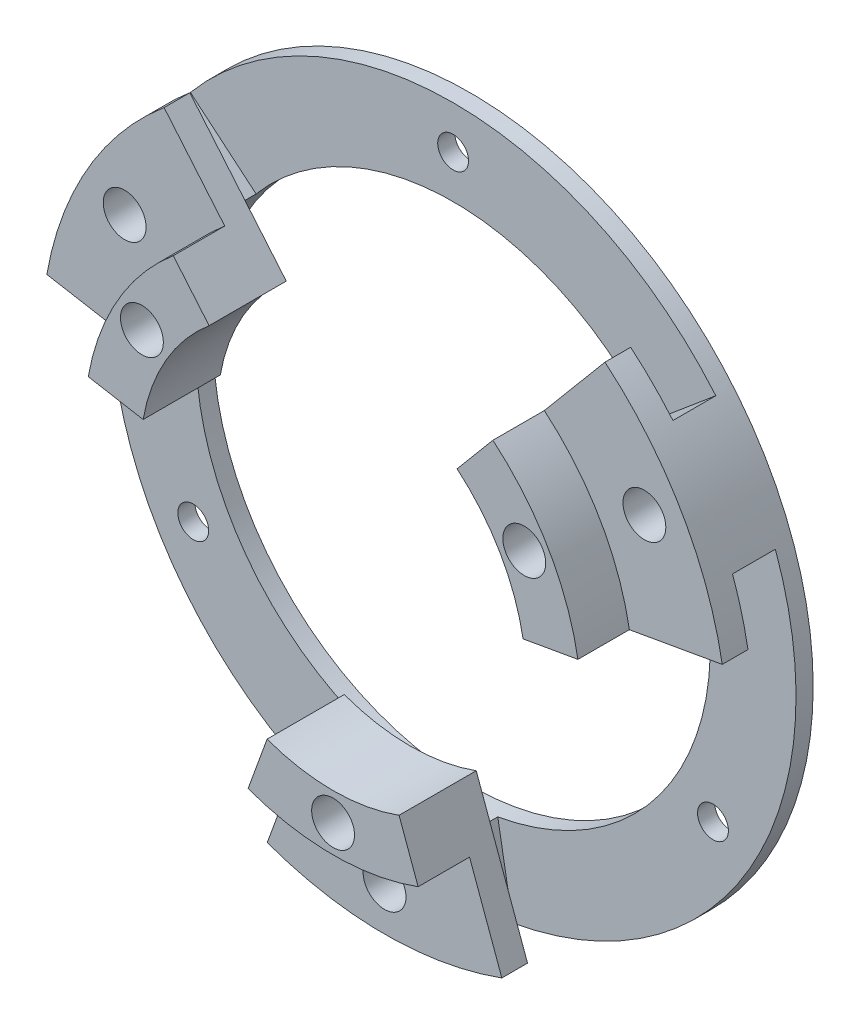
SolidWorks part; units mm, degrees
ref_plane "前视基准面" through (0, 0, 0) normal (0, 0, 1) x (1, 0, 0)
ref_plane "上视基准面" through (0, 0, 0) normal (0, 1, 0) x (1, 0, 0)
ref_plane "右视基准面" through (0, 0, 0) normal (1, 0, 0) x (0, 0, -1)
other "Configuration Table"
sketch "草图1" plane through (0, 0, 0) normal (0, 0, 1) x (1, 0, 0)
  circle A0 centre (0, 0) radius 40
  circle A1 centre (0, 0) radius 35 construction
  circle A2 centre (0, 0) radius 30
  dimension "D1" = 70
  dimension "D2" = 80
  dimension "D3" = 60
extrude "凸台-拉伸1" add sketch "草图1" along normal blind 2
sketch "草图2" plane through (0, 0, 2) normal (0, 0, 1) x (1, 0, 0)
  line L0 (0, 40) -> (0, 30) construction
  line L1 (34.641, -20) -> (25.9808, -15) construction
  line L2 (-34.641, -20) -> (-25.9808, -15) construction
  circle A0 centre (0, 0) radius 40 construction
  circle A1 centre (0, 0) radius 30 construction
  circle A2 centre (0, 0) radius 40 construction
  circle A3 centre (0, 35) radius 1.8
  circle A4 centre (30.3109, -17.5) radius 1.8
  circle A5 centre (-30.3109, -17.5) radius 1.8
  point P9 (0, 0)
  point P22 (0, 0)
  dimension "D2" = 3.6
  dimension "D4" = 35
  dimension "D1" = 3
  dimension "D3" = 3
extrude "切除-拉伸1" cut sketch "草图2" against normal up to next
sketch "草图3" plane through (0, 0, 2) normal (0, 0, 1) x (1, 0, 0)
  line L0 (0, 35) -> (0, 0) construction
  line L1 (25.9808, 15) -> (34.641, 20) construction
  line L2 (22.9813, 19.2836) -> (30.6418, 25.7115)
  line L3 (28.1908, 10.2606) -> (37.5877, 13.6808)
  line L4 (5.2094, -29.5442) -> (6.9459, -39.3923)
  line L5 (-5.2094, -29.5442) -> (-6.9459, -39.3923)
  line L6 (-28.1908, 10.2606) -> (-37.5877, 13.6808)
  line L7 (-22.9813, 19.2836) -> (-30.6418, 25.7115)
  circle A0 centre (0, 0) radius 40
  circle A1 centre (0, 35) radius 1.8 construction
  circle A2 centre (0, 35) radius 1.8
  circle A3 centre (0, 0) radius 40 construction
  circle A4 centre (0, 0) radius 30
  circle A5 centre (0, 0) radius 40
  circle A6 centre (0, 0) radius 40
  point P27 (0, 0)
  dimension "D1" = 60
  dimension "D2" = 10
  dimension "D3" = 3
extrude "凸台-拉伸3" add sketch "草图3" along normal blind 5 contours L7 L6 | L7 L3 L6 L2 | L7 L5 L6 L4
sketch "草图4" plane through (0, 0, 7) normal (0, 0, 1) x (1, 0, 0)
  line L12 (-19.2836, 22.9813) -> (-25.7115, 30.6418)
  line L13 (-34.641, 20) -> (-25.9808, 15) construction
  line L14 (-29.5442, 5.2094) -> (-39.3923, 6.9459)
  line L15 (29.5442, 5.2094) -> (39.3923, 6.9459)
  line L16 (19.2836, 22.9813) -> (25.7115, 30.6418)
  line L17 (-10.2606, -28.1908) -> (-13.6808, -37.5877)
  line L18 (10.2606, -28.1908) -> (13.6808, -37.5877)
  arc A0 (-5.2094, -29.5442) -> (5.2094, -29.5442) centre (0, 0) ccw construction
  arc A1 (-6.9459, -39.3923) -> (6.9459, -39.3923) centre (0, 0) ccw construction
  arc A2 (28.1908, 10.2606) -> (22.9813, 19.2836) centre (0, 0) ccw construction
  arc A3 (37.5877, 13.6808) -> (30.6418, 25.7115) centre (0, 0) ccw construction
  arc A4 (-22.9813, 19.2836) -> (-28.1908, 10.2606) centre (0, 0) ccw construction
  arc A5 (-30.6418, 25.7115) -> (-37.5877, 13.6808) centre (0, 0) ccw construction
  arc A6 (-5.2094, -29.5442) -> (5.2094, -29.5442) centre (0, 0) ccw
  arc A7 (-6.9459, -39.3923) -> (6.9459, -39.3923) centre (0, 0) ccw
  arc A8 (28.1908, 10.2606) -> (22.9813, 19.2836) centre (0, 0) ccw
  arc A9 (37.5877, 13.6808) -> (30.6418, 25.7115) centre (0, 0) ccw
  arc A10 (-22.9813, 19.2836) -> (-28.1908, 10.2606) centre (0, 0) ccw
  arc A11 (-30.6418, 25.7115) -> (-37.5877, 13.6808) centre (0, 0) ccw
  circle A12 centre (0, 0) radius 30 construction
  circle A13 centre (0, 0) radius 40 construction
  circle A14 centre (0, 0) radius 30
  circle A15 centre (0, 0) radius 40
  point P40 (0, 0)
  arc M17 (-28.1908, 10.2606) -> (-22.9813, 19.2836) centre (0, 0) cw
  line M18 (-22.9813, 19.2836) -> (-30.6418, 25.7115)
  arc M19 (-30.6418, 25.7115) -> (-37.5877, 13.6808) centre (0, 0) ccw
  line M20 (-37.5877, 13.6808) -> (-28.1908, 10.2606)
  dimension "D1" = 20
  dimension "D2" = 3
extrude "凸台-拉伸4" add sketch "草图4" along normal blind 3 contours L12 A15 A14 M18 | L13 A14 M19 M18 | L13 A15 M20 M17 | A15 L14 A14 M20 | A9 A15 L16 A14 A8 L15 | L17 A15 A7 L18 A14 A6
sketch "草图5" plane through (0, 0, 10) normal (0, 0, 1) x (1, 0, 0)
  line L0 (-34.641, 20) -> (-25.9808, 15) construction
  line L2 (-19.2836, 22.9813) -> (-25.7115, 30.6418)
  line L3 (-39.3923, 6.9459) -> (-29.5442, 5.2094)
  line L4 (-19.2836, 22.9813) -> (-25.7115, 30.6418) construction
  line L5 (-39.3923, 6.9459) -> (-29.5442, 5.2094) construction
  circle A0 centre (-30.3109, 17.5) radius 2.5
  circle A1 centre (30.3109, 17.5) radius 2.5
  arc A2 (-25.7115, 30.6418) -> (-39.3923, 6.9459) centre (0, 0) ccw
  arc A3 (-19.2836, 22.9813) -> (-29.5442, 5.2094) centre (0, 0) ccw
  arc A4 (-25.7115, 30.6418) -> (-39.3923, 6.9459) centre (0, 0) ccw construction
  arc A5 (-19.2836, 22.9813) -> (-29.5442, 5.2094) centre (0, 0) ccw construction
  circle A6 centre (0, -35) radius 2.5
  point P16 (0, 0)
  dimension "D2" = 5
  dimension "D1" = 0
  dimension "D3" = 3
extrude "切除-拉伸2" cut sketch "草图5" against normal up to next
sketch "草图6" plane through (0, 0, 10) normal (0, 0, 1) x (1, 0, 0)
  line L0 (-10.2606, -28.1908) -> (-13.6808, -37.5877) construction
  line L1 (13.6808, -37.5877) -> (10.2606, -28.1908) construction
  line L2 (-19.2836, 22.9813) -> (-25.7115, 30.6418) construction
  line L3 (-39.3923, 6.9459) -> (-29.5442, 5.2094) construction
  line L4 (25.7115, 30.6418) -> (19.2836, 22.9813) construction
  line L5 (29.5442, 5.2094) -> (39.3923, 6.9459) construction
  line L6 (-10.2606, -28.1908) -> (-13.6808, -37.5877) construction
  line L7 (13.6808, -37.5877) -> (10.2606, -28.1908) construction
  line L8 (-19.2836, 22.9813) -> (-25.7115, 30.6418) construction
  line L9 (-39.3923, 6.9459) -> (-29.5442, 5.2094) construction
  line L10 (25.7115, 30.6418) -> (19.2836, 22.9813) construction
  line L11 (29.5442, 5.2094) -> (39.3923, 6.9459) construction
  line L12 (-19.4856, 11.25) -> (-25.9808, 15) construction
  line L13 (-14.4627, 17.236) -> (-19.2836, 22.9813)
  line L14 (-22.1582, 3.9071) -> (-29.5442, 5.2094)
  line L15 (22.1582, 3.9071) -> (29.5442, 5.2094)
  line L16 (14.4627, 17.236) -> (19.2836, 22.9813)
  line L17 (-7.6955, -21.1431) -> (-10.2606, -28.1908)
  line L18 (7.6955, -21.1431) -> (10.2606, -28.1908)
  arc A0 (-13.6808, -37.5877) -> (13.6808, -37.5877) centre (0, 0) ccw construction
  arc A1 (-10.2606, -28.1908) -> (10.2606, -28.1908) centre (0, 0) ccw construction
  arc A2 (-25.7115, 30.6418) -> (-39.3923, 6.9459) centre (0, 0) ccw construction
  arc A3 (-19.2836, 22.9813) -> (-29.5442, 5.2094) centre (0, 0) ccw construction
  arc A4 (39.3923, 6.9459) -> (25.7115, 30.6418) centre (0, 0) ccw construction
  arc A5 (29.5442, 5.2094) -> (19.2836, 22.9813) centre (0, 0) ccw construction
  arc A6 (-13.6808, -37.5877) -> (13.6808, -37.5877) centre (0, 0) ccw construction
  arc A7 (-10.2606, -28.1908) -> (10.2606, -28.1908) centre (0, 0) ccw
  arc A8 (-25.7115, 30.6418) -> (-39.3923, 6.9459) centre (0, 0) ccw construction
  arc A9 (-19.2836, 22.9813) -> (-29.5442, 5.2094) centre (0, 0) ccw
  arc A10 (39.3923, 6.9459) -> (25.7115, 30.6418) centre (0, 0) ccw construction
  arc A11 (29.5442, 5.2094) -> (19.2836, 22.9813) centre (0, 0) ccw
  arc A12 (-7.6955, -21.1431) -> (7.6955, -21.1431) centre (0, 0) ccw
  arc A13 (-14.4627, 17.236) -> (-22.1582, 3.9071) centre (0, 0) ccw
  arc A14 (22.1582, 3.9071) -> (14.4627, 17.236) centre (0, 0) ccw
  point P23 (0, 0)
  dimension "D1" = 45
  dimension "D2" = 3
extrude "凸台-拉伸5" add sketch "草图6" along normal blind 6 and the other way up to surface
sketch "草图7" plane through (0, 0, 16) normal (0, 0, 1) x (1, 0, 0)
  line L0 (10.2606, -28.1908) -> (7.6955, -21.1431) construction
  line L1 (-7.6955, -21.1431) -> (-10.2606, -28.1908) construction
  line L2 (-14.4627, 17.236) -> (-19.2836, 22.9813) construction
  line L3 (-29.5442, 5.2094) -> (-22.1582, 3.9071) construction
  line L4 (19.2836, 22.9813) -> (14.4627, 17.236) construction
  line L5 (22.1582, 3.9071) -> (29.5442, 5.2094) construction
  line L6 (10.2606, -28.1908) -> (7.6955, -21.1431)
  line L7 (-7.6955, -21.1431) -> (-10.2606, -28.1908)
  line L8 (-14.4627, 17.236) -> (-19.2836, 22.9813)
  line L9 (-29.5442, 5.2094) -> (-22.1582, 3.9071)
  line L10 (19.2836, 22.9813) -> (14.4627, 17.236)
  line L11 (22.1582, 3.9071) -> (29.5442, 5.2094)
  arc A0 (-10.2606, -28.1908) -> (10.2606, -28.1908) centre (0, 0) ccw construction
  arc A1 (-7.6955, -21.1431) -> (7.6955, -21.1431) centre (0, 0) ccw construction
  arc A2 (-14.4627, 17.236) -> (-22.1582, 3.9071) centre (0, 0) ccw construction
  arc A3 (-19.2836, 22.9813) -> (-29.5442, 5.2094) centre (0, 0) ccw construction
  arc A4 (29.5442, 5.2094) -> (19.2836, 22.9813) centre (0, 0) ccw construction
  arc A5 (22.1582, 3.9071) -> (14.4627, 17.236) centre (0, 0) ccw construction
  arc A6 (-10.2606, -28.1908) -> (10.2606, -28.1908) centre (0, 0) ccw
  arc A7 (-7.6955, -21.1431) -> (7.6955, -21.1431) centre (0, 0) ccw
  arc A8 (-14.4627, 17.236) -> (-22.1582, 3.9071) centre (0, 0) ccw
  arc A9 (-19.2836, 22.9813) -> (-29.5442, 5.2094) centre (0, 0) ccw
  arc A10 (29.5442, 5.2094) -> (19.2836, 22.9813) centre (0, 0) ccw
  arc A11 (22.1582, 3.9071) -> (14.4627, 17.236) centre (0, 0) ccw
  circle A12 centre (0, 0) radius 29
  arc M6 (29.5442, 5.2094) -> (19.2836, 22.9813) centre (0, 0) ccw
  line M7 (19.2836, 22.9813) -> (14.4627, 17.236)
  dimension "D1" = 1
extrude "切除-拉伸3" cut sketch "草图7" against normal up to surface (6 mm away) contours A12 L8 A9 L9 | A12 L11 M6 M7 | A12 L7 A6 L6 up to face at (2.5, -35, 10)
sketch "草图8" plane through (0, 0, 16) normal (0, 0, 1) x (1, 0, 0)
  line L0 (-14.4627, 17.236) -> (-18.6408, 22.2153) construction
  line L1 (-14.4627, 17.236) -> (-18.6408, 22.2153)
  line L2 (-28.5594, 5.0358) -> (-22.1582, 3.9071) construction
  line L3 (-28.5594, 5.0358) -> (-22.1582, 3.9071)
  line L4 (-25.1147, 14.5) -> (-19.4856, 11.25)
  arc A0 (-18.6408, 22.2153) -> (-28.5594, 5.0358) centre (0, 0) ccw
  arc A1 (-14.4627, 17.236) -> (-22.1582, 3.9071) centre (0, 0) ccw
  circle A2 centre (0, 0) radius 22.5 construction
  circle A3 centre (0, 0) radius 29 construction
  circle A4 centre (-22.3002, 12.875) radius 2.5
  circle A5 centre (22.3002, 12.875) radius 2.5
  circle A6 centre (0, -25.75) radius 2.5
  point P10 (-22.3002, 12.875)
  point P19 (0, 0)
  dimension "D1" = 45
  dimension "D2" = 58
  dimension "D5" = 5
  dimension "D3" = 25.75
  dimension "D4" = 20
extrude "切除-拉伸4" cut sketch "草图8" against normal up to next contours A6 | A5 | L4 A4 | L4 A4
